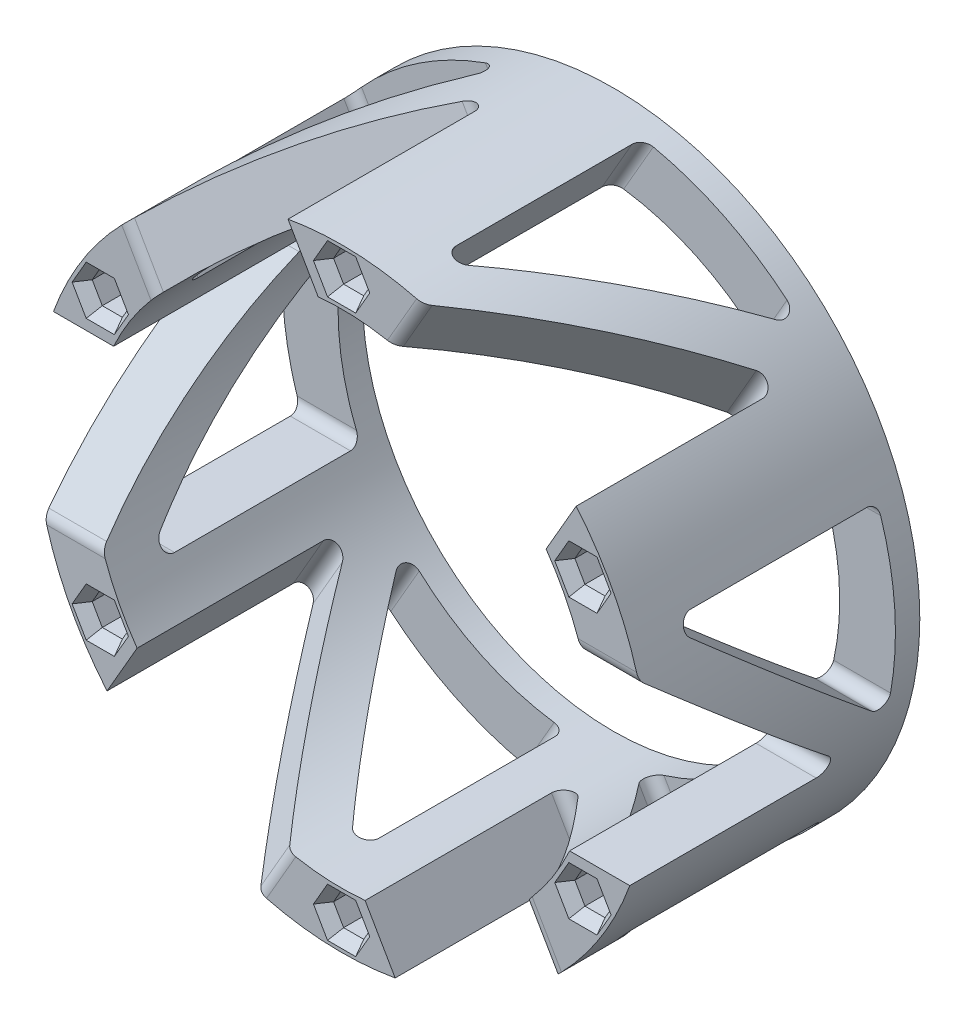
SolidWorks part; units mm, degrees
ref_plane "前视基准面" through (0, 0, 0) normal (0, 0, 1) x (1, 0, 0)
ref_plane "上视基准面" through (0, 0, 0) normal (0, 1, 0) x (1, 0, 0)
ref_plane "右视基准面" through (0, 0, 0) normal (1, 0, 0) x (0, 0, -1)
sketch "草图1" plane through (0, 0, 0) normal (0, 0, 1) x (1, 0, 0)
  line L0 (36.0844, 17.5) -> (37.5278, 20)
  line L1 (2.8868, 40) -> (1.4434, 42.5)
  line L2 (1.4434, 42.5) -> (-1.4434, 42.5)
  line L3 (-1.4434, 42.5) -> (-2.8868, 40)
  line L4 (-2.8868, 40) -> (-1.4434, 37.5)
  line L5 (-1.4434, 37.5) -> (1.4434, 37.5)
  line L6 (1.4434, 37.5) -> (2.8868, 40)
  line L7 (37.5278, 20) -> (36.0844, 22.5)
  line L8 (36.0844, 22.5) -> (33.1976, 22.5)
  line L9 (33.1976, 22.5) -> (31.7543, 20)
  line L10 (31.7543, 20) -> (33.1976, 17.5)
  line L11 (33.1976, 17.5) -> (36.0844, 17.5)
  line L12 (33.1976, -22.5) -> (36.0844, -22.5)
  line L13 (36.0844, -22.5) -> (37.5278, -20)
  line L14 (37.5278, -20) -> (36.0844, -17.5)
  line L15 (36.0844, -17.5) -> (33.1976, -17.5)
  line L16 (33.1976, -17.5) -> (31.7543, -20)
  line L17 (31.7543, -20) -> (33.1976, -22.5)
  line L18 (-2.8868, -40) -> (-1.4434, -42.5)
  line L19 (-1.4434, -42.5) -> (1.4434, -42.5)
  line L20 (1.4434, -42.5) -> (2.8868, -40)
  line L21 (2.8868, -40) -> (1.4434, -37.5)
  line L22 (1.4434, -37.5) -> (-1.4434, -37.5)
  line L23 (-1.4434, -37.5) -> (-2.8868, -40)
  line L24 (-36.0844, -17.5) -> (-37.5278, -20)
  line L25 (-37.5278, -20) -> (-36.0844, -22.5)
  line L26 (-36.0844, -22.5) -> (-33.1976, -22.5)
  line L27 (-33.1976, -22.5) -> (-31.7543, -20)
  line L28 (-31.7543, -20) -> (-33.1976, -17.5)
  line L29 (-33.1976, -17.5) -> (-36.0844, -17.5)
  line L30 (-33.1976, 22.5) -> (-36.0844, 22.5)
  line L31 (-36.0844, 22.5) -> (-37.5278, 20)
  line L32 (-37.5278, 20) -> (-36.0844, 17.5)
  line L33 (-36.0844, 17.5) -> (-33.1976, 17.5)
  line L34 (-33.1976, 17.5) -> (-31.7543, 20)
  line L35 (-31.7543, 20) -> (-33.1976, 22.5)
  circle A0 centre (0, 0) radius 36
  circle A1 centre (0, 0) radius 40 construction
  circle A2 centre (0, 0) radius 44
  circle A4 centre (0, 40) radius 2.5 construction
  point P45 (0, 0)
  dimension "D1" = 72
  dimension "D2" = 88
  dimension "D3" = 80
  dimension "D4" = 5
  dimension "D5" = 6
extrude "凸台-拉伸1" add sketch "草图1" along normal blind 39
sketch "草图3" plane through (0, 0, 0) normal (0, 0, -1) x (-1, 0, 0)
  line L0 (-34.641, 20) -> (0, 0) construction
  line L1 (0, 0) -> (-34.641, -20) construction
  line L2 (0, 0) -> (-36, 0) construction
  circle A0 centre (0, 0) radius 36 construction
  dimension "D1" = 40
  dimension "D2" = 60
sketch "草图7" plane through (0, 0, 0) normal (1, 0, 0) x (0, 0, -1)
  line L1 (-30.2532, -15) -> (-5, -15)
  line L2 (-39, -11.0722) -> (-39, 15)
  line L3 (-39, 15) -> (-12.2468, 15)
  line L4 (-3.5, -13.5) -> (-3.5, 7.8408)
  line L5 (-39, 44) -> (-39, -44) construction
  line L6 (-11.2786, 12.3543) -> (-39, -11.0722)
  line L7 (-31.2214, -12.3543) -> (-5.9682, 8.9864)
  line L8 (-39, -11.0722) -> (-39, -15) construction
  line L9 (-39, -15) -> (-34.3522, -15) construction
  line L10 (-3.5, 15) -> (-39, -15) construction
  line L11 (-8.1478, 15) -> (-3.5, 15) construction
  line L12 (-3.5, 15) -> (-3.5, 11.0722) construction
  line L13 (0, 20) -> (0, 0) construction
  arc A0 (-5.9682, 8.9864) -> (-3.5, 7.8408) centre (-5, 7.8408) cw
  arc A1 (-31.2214, -12.3543) -> (-30.2532, -15) centre (-30.2532, -13.5) ccw
  arc A2 (-5, -15) -> (-3.5, -13.5) centre (-5, -13.5) ccw
  arc A3 (-11.2786, 12.3543) -> (-12.2468, 15) centre (-12.2468, 13.5) ccw
  dimension "D5" = 1.5
  dimension "D7" = 1.5
  dimension "D1" = 3.5
  dimension "D2" = 30
  dimension "D3" = 3
  dimension "D4" = 3
  dimension "D6" = 15
extrude "切除-拉伸6" cut sketch "草图7" against normal blind 59
fillet "圆角1" radius 2 1 edges at (-38.4196, -11.0722, 39)
pattern_circular "阵列(圆周)1" count 6 over 360 about axis through (0, 0, 0) along (0, 0, 1) of "切除-拉伸6", "圆角1"
sketch "草图8" plane through (0, 0, 0) normal (0, 0, 1) x (1, 0, 0)
  line L0 (-1.4434, 42.5) -> (-2.8868, 40) construction
  line L1 (-2.8868, 40) -> (-1.4434, 37.5) construction
  line L2 (-1.4434, 37.5) -> (1.4434, 37.5) construction
  line L3 (1.4434, 37.5) -> (2.8868, 40) construction
  line L4 (2.8868, 40) -> (1.4434, 42.5) construction
  line L5 (1.4434, 42.5) -> (-1.4434, 42.5) construction
  line L6 (-1.4434, 42.5) -> (-2.8868, 40)
  line L7 (-2.8868, 40) -> (-1.4434, 37.5)
  line L8 (-1.4434, 37.5) -> (1.4434, 37.5)
  line L9 (1.4434, 37.5) -> (2.8868, 40)
  line L10 (2.8868, 40) -> (1.4434, 42.5)
  line L11 (1.4434, 42.5) -> (-1.4434, 42.5)
  line L12 (36.0844, 22.5) -> (33.1976, 22.5)
  line L13 (33.1976, 22.5) -> (31.7543, 20)
  line L14 (31.7543, 20) -> (33.1976, 17.5)
  line L15 (33.1976, 17.5) -> (36.0844, 17.5)
  line L16 (36.0844, 17.5) -> (37.5278, 20)
  line L17 (37.5278, 20) -> (36.0844, 22.5)
  line L18 (37.5278, -20) -> (36.0844, -17.5)
  line L19 (36.0844, -17.5) -> (33.1976, -17.5)
  line L20 (33.1976, -17.5) -> (31.7543, -20)
  line L21 (31.7543, -20) -> (33.1976, -22.5)
  line L22 (33.1976, -22.5) -> (36.0844, -22.5)
  line L23 (36.0844, -22.5) -> (37.5278, -20)
  line L24 (1.4434, -42.5) -> (2.8868, -40)
  line L25 (2.8868, -40) -> (1.4434, -37.5)
  line L26 (1.4434, -37.5) -> (-1.4434, -37.5)
  line L27 (-1.4434, -37.5) -> (-2.8868, -40)
  line L28 (-2.8868, -40) -> (-1.4434, -42.5)
  line L29 (-1.4434, -42.5) -> (1.4434, -42.5)
  line L30 (-36.0844, -22.5) -> (-33.1976, -22.5)
  line L31 (-33.1976, -22.5) -> (-31.7543, -20)
  line L32 (-31.7543, -20) -> (-33.1976, -17.5)
  line L33 (-33.1976, -17.5) -> (-36.0844, -17.5)
  line L34 (-36.0844, -17.5) -> (-37.5278, -20)
  line L35 (-37.5278, -20) -> (-36.0844, -22.5)
  line L36 (-37.5278, 20) -> (-36.0844, 17.5)
  line L37 (-36.0844, 17.5) -> (-33.1976, 17.5)
  line L38 (-33.1976, 17.5) -> (-31.7543, 20)
  line L39 (-31.7543, 20) -> (-33.1976, 22.5)
  line L40 (-33.1976, 22.5) -> (-36.0844, 22.5)
  line L41 (-36.0844, 22.5) -> (-37.5278, 20)
  circle A0 centre (0, 40) radius 1.6
  circle A1 centre (34.641, 20) radius 1.6
  circle A2 centre (34.641, -20) radius 1.6
  circle A3 centre (0, -40) radius 1.6
  circle A4 centre (-34.641, -20) radius 1.6
  circle A5 centre (-34.641, 20) radius 1.6
  point P52 (0, 0)
  dimension "D1" = 3.2
  dimension "D2" = 6
extrude "凸台-拉伸2" add sketch "草图8" along normal blind 6.7
chamfer "倒角1" distance 1 angle 60 36 edges at (-36.8061, 21.25, 39) (-36.8061, 18.75, 39) (-34.641, 17.5, 39) (-32.476, 18.75, 39) (-32.476, 21.25, 39) (-34.641, 22.5, 39) (-36.8061, -21.25, 39) (-34.641, -22.5, 39) (-32.476, -21.25, 39) (-32.476, -18.75, 39) (-34.641, -17.5, 39) (-36.8061, -18.75, 39) (0, -42.5, 39) (2.1651, -41.25, 39) (2.1651, -38.75, 39) (0, -37.5, 39) (-2.1651, -38.75, 39) (-2.1651, -41.25, 39) (36.8061, -21.25, 39) (36.8061, -18.75, 39) (34.641, -17.5, 39) (32.476, -18.75, 39) (32.476, -21.25, 39) (34.641, -22.5, 39) (36.8061, 21.25, 39) (34.641, 22.5, 39) (32.476, 21.25, 39) (32.476, 18.75, 39) (34.641, 17.5, 39) (36.8061, 18.75, 39) (0, 42.5, 39) (-2.1651, 41.25, 39) (-2.1651, 38.75, 39) (0, 37.5, 39) (2.1651, 38.75, 39) (2.1651, 41.25, 39)
